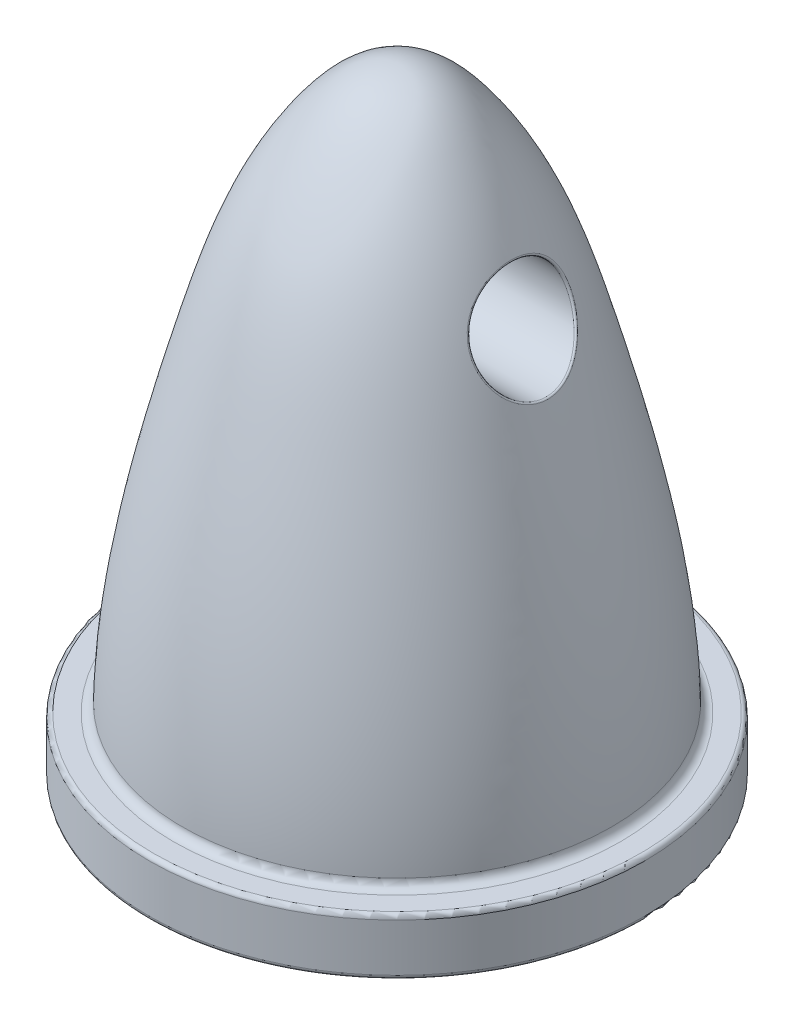
SolidWorks part; units mm, degrees
material "6061 Alloy"
ref_plane "Front" through (0, 0, 0) normal (0, 0, 1) x (1, 0, 0)
ref_plane "Top" through (0, 0, 0) normal (0, 1, 0) x (1, 0, 0)
ref_plane "Right" through (0, 0, 0) normal (1, 0, 0) x (0, 0, -1)
sketch "Sketch1" plane through (0, 0, 0) normal (0, 0, 1) x (1, 0, 0)
  line L0 (0, 0) -> (0, 18.0594) construction
  line L1 (7.239, 1.651) -> (6.2738, 1.651)
  line L2 (0, 0) -> (7.239, 0)
  line L3 (0, 0) -> (0, 1.651)
  line L4 (0, 18.0594) -> (0, 1.651)
  line L5 (7.239, 0) -> (7.239, 1.651)
  spline S0 degree 3 poles (0, 18.0594) (1.0011, 18.0594) (3.2322, 15.733) (4.9889, 10.0436) (6.2738, 4.5629) (6.2738, 1.651) knots 0 0 0 0 0.146163 0.478561 1 1 1 1
  dimension "D1" = 7.239
  dimension "D2" = 1.651
  dimension "D3" = 0.9652
  dimension "D4" = 18.0594
revolve "Revolve1" add sketch "Sketch1" angle 360 about L0
fillet "Fillet1" radius 0.254 1 edges at (0, 1.651, -6.2738)
sketch "Sketch2" plane through (0, 0, 0) normal (1, 0, 0) x (0, 0, -1)
  line L0 (-7.239, 0) -> (7.239, 0) construction
  circle A0 centre (0, 13.2588) radius 1.4351
  dimension "D1" = 2.8702
  dimension "D2" = 13.2588
extrude "Cut-Extrude1" cut sketch "Sketch2" against normal through all both and the other way through all
fillet "Fillet2" radius 0.0508 2 edges at (3.36, 14.6722, 0.2483) (-3.5488, 13.6137, 1.3905)
sketch "Sketch3" plane through (0, 0, 0) normal (0, -1, 0) x (1, 0, 0)
  circle A0 centre (0, 0) radius 2.54
  dimension "D1" = 5.08
extrude "Cut-Extrude2" cut sketch "Sketch3" against normal blind 9.7028
fillet "Fillet3" radius 0.127 3 edges at (0, 0, -2.54) (0, 1.651, -7.239) (0, 0, -7.239)
